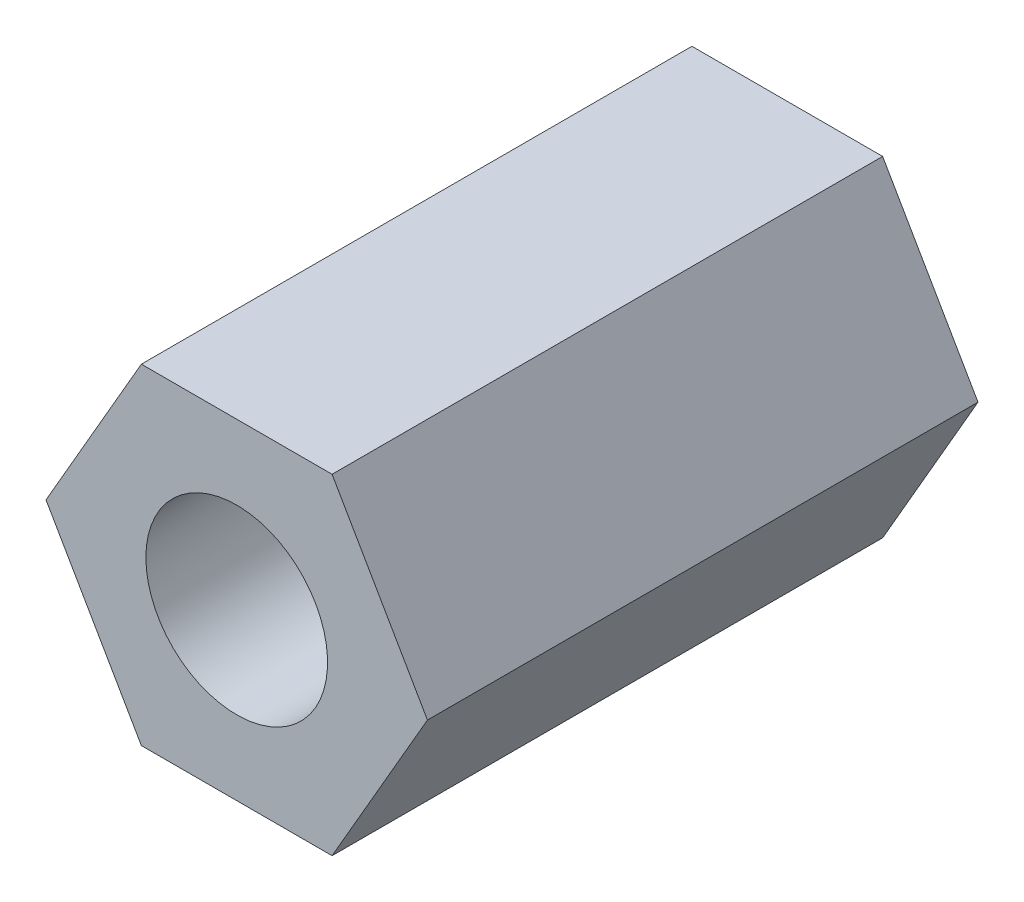
SolidWorks part; units mm, degrees
ref_plane "前视基准面" through (0, 0, 0) normal (0, 0, 1) x (1, 0, 0)
ref_plane "上视基准面" through (0, 0, 0) normal (0, 1, 0) x (1, 0, 0)
ref_plane "右视基准面" through (0, 0, 0) normal (1, 0, 0) x (0, 0, -1)
sketch "草图1" plane through (0, 0, 0) normal (0, 0, 1) x (1, 0, 0)
  line L0 (0, 0) -> (4.3863, 0) construction
  line L1 (0, 0) -> (0, 4.0694) construction
  line L3 (3.4641, 0) -> (1.7321, 3)
  line L4 (1.7321, 3) -> (-1.7321, 3)
  line L5 (-1.7321, 3) -> (-3.4641, 0)
  line L6 (-3.4641, 0) -> (-1.7321, -3)
  line L7 (-1.7321, -3) -> (1.7321, -3)
  line L8 (1.7321, -3) -> (3.4641, 0)
  circle A0 centre (0, 0) radius 3 construction
  dimension "D1" = 6
extrude "凸台-拉伸1" add sketch "草图1" along normal blind 10
sketch "草图4" plane through (0, 0, 0) normal (0, 0, -1) x (-1, 0, 0)
  point P0 (0, 0)
hole_wizard "M4 螺纹孔1" positions "草图4" profile "草图5" tap size "M4" standard "GB" end condition through all
sketch "草图5" plane through (0, 0, 0) normal (1, 0, 0) x (0, 1, 0)
  line L0 (0, 0) -> (0, 10)
  line L1 (0, 10) -> (1.65, 10)
  line L2 (1.65, 10) -> (1.65, 0.375)
  line L3 (1.65, 0.375) -> (2.025, 0)
  line L5 (2.025, 0) -> (0, 0)
  line L6 (-1.65, 0.375) -> (-2.025, 0) construction
  line L11 (0, -6.35) -> (0, 107.95) construction
  dimension "通孔螺纹孔钻头直径" = 3.3
  dimension "通孔螺纹孔钻头深度" = 10
  dimension "近端锥形沉头孔直径" = 4.05
  dimension "近端锥形沉头孔角度" = 90
